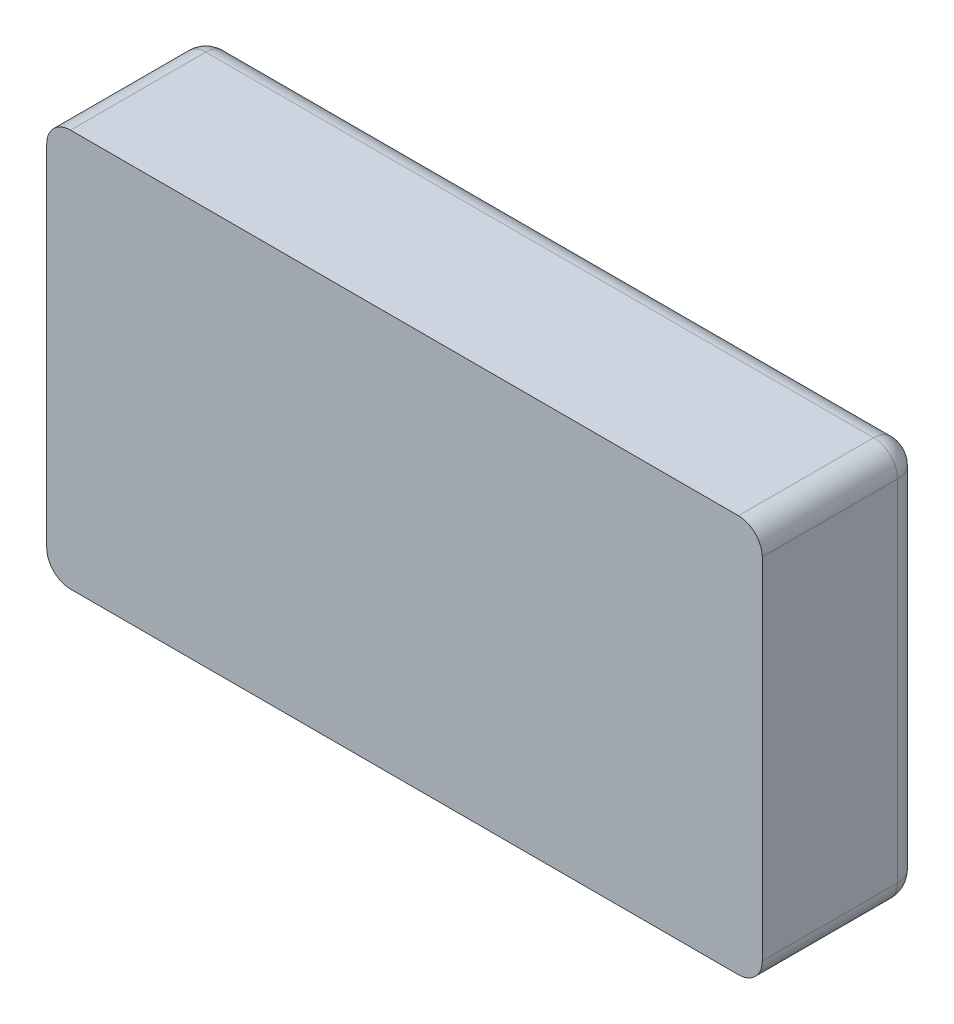
SolidWorks part; units mm, degrees
ref_plane "Front Plane" through (0, 0, 0) normal (0, 0, 1) x (1, 0, 0)
ref_plane "Top Plane" through (0, 0, 0) normal (0, 1, 0) x (1, 0, 0)
ref_plane "Right Plane" through (0, 0, 0) normal (1, 0, 0) x (0, 0, -1)
sketch "Sketch1" plane through (0, 0, 0) normal (0, 0, 1) x (1, 0, 0)
  line L1 (0, 0) -> (9, 0)
  line L2 (0, 0) -> (0, -5)
  line L3 (0, -5) -> (9, -5)
  line L4 (9, 0) -> (9, -5)
  dimension "D1" = 9
  dimension "D2" = 5
extrude "Boss-Extrude1" add sketch "Sketch1" along normal blind 2
fillet "Fillet7" radius 0.3 1 edges at (0, 0, 1)
fillet "Fillet8" radius 0.3 3 edges at (0, -2.65, 0) (0.0879, -0.0879, 0) (4.65, 0, 0)
fillet "Fillet9" radius 0.3 3 edges at (9, -2.65, 0) (9, -0.0879, 0.0879) (9, 0, 1.15)
fillet "Fillet10" radius 0.3 5 edges at (0, -5, 1.15) (0.0879, -5, 0.0879) (9, -5, 1.15) (8.9121, -5, 0.0879) (4.5, -5, 0)
